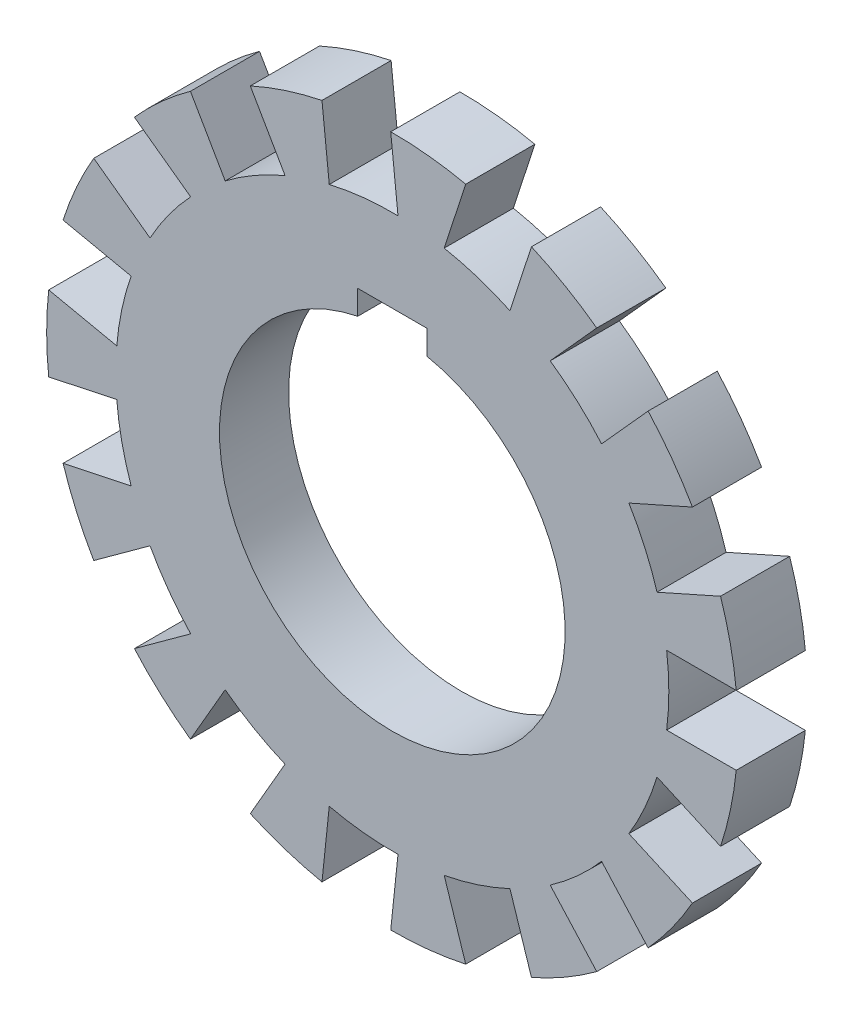
SolidWorks part; units mm, degrees
material "6061-T6 (SS)"
ref_plane "Front Plane" through (0, 0, 0) normal (0, 0, 1) x (1, 0, 0)
ref_plane "Top Plane" through (0, 0, 0) normal (0, 1, 0) x (1, 0, 0)
ref_plane "Right Plane" through (0, 0, 0) normal (1, 0, 0) x (0, 0, -1)
sketch "Sketch1" plane through (0, 0, 0) normal (0, 0, 1) x (1, 0, 0)
  line L0 (39.6863, -5) -> (49.7494, -5)
  line L1 (39.6863, 5) -> (49.7494, 5)
  line L2 (38.2889, -11.5741) -> (47.482, -15.6672)
  line L3 (34.2215, -20.7096) -> (43.4146, -24.8026)
  line L4 (30.271, -26.147) -> (37.0046, -33.6253)
  line L5 (22.8396, -32.8383) -> (29.5731, -40.3166)
  line L6 (17.019, -36.1988) -> (20.1287, -45.7694)
  line L7 (7.5084, -39.289) -> (10.6181, -48.8595)
  line L8 (0.8243, -39.9915) -> (-0.2276, -49.9995)
  line L9 (-9.121, -38.9462) -> (-10.1728, -48.9542)
  line L10 (-15.513, -36.8693) -> (-20.5446, -45.5842)
  line L11 (-24.1733, -31.8693) -> (-29.2048, -40.5842)
  line L12 (-29.1679, -27.3721) -> (-37.3092, -33.287)
  line L13 (-35.0458, -19.2819) -> (-43.187, -25.1969)
  line L14 (-37.7795, -13.142) -> (-47.6227, -15.2342)
  line L15 (-39.8586, -3.3605) -> (-49.7018, -5.4527)
  line L16 (-39.8586, 3.3605) -> (-49.7018, 5.4527)
  line L17 (-37.7795, 13.142) -> (-47.6227, 15.2342)
  line L18 (-35.0458, 19.2819) -> (-43.187, 25.1969)
  line L19 (-29.1679, 27.3721) -> (-37.3092, 33.287)
  line L20 (-24.1733, 31.8693) -> (-29.2048, 40.5842)
  line L21 (-15.513, 36.8693) -> (-20.5446, 45.5842)
  line L22 (-9.121, 38.9462) -> (-10.1728, 48.9542)
  line L23 (0.8243, 39.9915) -> (-0.2276, 49.9995)
  line L24 (7.5084, 39.289) -> (10.6181, 48.8595)
  line L25 (17.019, 36.1988) -> (20.1287, 45.7694)
  line L26 (22.8396, 32.8383) -> (29.5731, 40.3166)
  line L27 (30.271, 26.147) -> (37.0046, 33.6253)
  line L28 (34.2215, 20.7096) -> (43.4146, 24.8026)
  line L29 (38.2889, 11.5741) -> (47.482, 15.6672)
  line L30 (-5, 24.4949) -> (-5, 28)
  line L31 (-5, 28) -> (5, 28)
  line L32 (5, 28) -> (5, 24.4949)
  arc A0 (39.6863, -5) -> (39.6863, 5) centre (0, 0) ccw
  arc A1 (-5, 24.4949) -> (5, 24.4949) centre (0, 0) ccw
  arc A2 (49.7494, 5) -> (47.482, 15.6672) centre (0, 0) ccw
  arc A3 (43.4146, 24.8026) -> (37.0046, 33.6253) centre (0, 0) ccw
  arc A4 (29.5731, 40.3166) -> (20.1287, 45.7694) centre (0, 0) ccw
  arc A5 (10.6181, 48.8595) -> (-0.2276, 49.9995) centre (0, 0) ccw
  arc A6 (-10.1728, 48.9542) -> (-20.5446, 45.5842) centre (0, 0) ccw
  arc A7 (-29.2048, 40.5842) -> (-37.3092, 33.287) centre (0, 0) ccw
  arc A8 (-43.187, 25.1969) -> (-47.6227, 15.2342) centre (0, 0) ccw
  arc A9 (-49.7018, 5.4527) -> (-49.7018, -5.4527) centre (0, 0) ccw
  arc A10 (-47.6227, -15.2342) -> (-43.187, -25.1969) centre (0, 0) ccw
  arc A11 (-37.3092, -33.287) -> (-29.2048, -40.5842) centre (0, 0) ccw
  arc A12 (-20.5446, -45.5842) -> (-10.1728, -48.9542) centre (0, 0) ccw
  arc A13 (-0.2276, -49.9995) -> (10.6181, -48.8595) centre (0, 0) ccw
  arc A14 (20.1287, -45.7694) -> (29.5731, -40.3166) centre (0, 0) ccw
  arc A15 (37.0046, -33.6253) -> (43.4146, -24.8026) centre (0, 0) ccw
  arc A16 (47.482, -15.6672) -> (49.7494, -5) centre (0, 0) ccw
  arc A17 (38.2889, 11.5741) -> (34.2215, 20.7096) centre (0, 0) ccw
  arc A18 (30.271, 26.147) -> (22.8396, 32.8383) centre (0, 0) ccw
  arc A19 (17.019, 36.1988) -> (7.5084, 39.289) centre (0, 0) ccw
  arc A20 (0.8243, 39.9915) -> (-9.121, 38.9462) centre (0, 0) ccw
  arc A21 (-15.513, 36.8693) -> (-24.1733, 31.8693) centre (0, 0) ccw
  arc A22 (-29.1679, 27.3721) -> (-35.0458, 19.2819) centre (0, 0) ccw
  arc A23 (-37.7795, 13.142) -> (-39.8586, 3.3605) centre (0, 0) ccw
  arc A24 (-39.8586, -3.3605) -> (-37.7795, -13.142) centre (0, 0) ccw
  arc A25 (-35.0458, -19.2819) -> (-29.1679, -27.3721) centre (0, 0) ccw
  arc A26 (-24.1733, -31.8693) -> (-15.513, -36.8693) centre (0, 0) ccw
  arc A27 (-9.121, -38.9462) -> (0.8243, -39.9915) centre (0, 0) ccw
  arc A28 (7.5084, -39.289) -> (17.019, -36.1988) centre (0, 0) ccw
  arc A29 (22.8396, -32.8383) -> (30.271, -26.147) centre (0, 0) ccw
  arc A30 (34.2215, -20.7096) -> (38.2889, -11.5741) centre (0, 0) ccw
  point P11 (0, 28)
  dimension "D1" = 80
  dimension "D2" = 50
  dimension "D5" = 100
  dimension "D3" = 10
  dimension "D4" = 5
  dimension "D6" = 15
  dimension "D7" = 28
  dimension "D8" = 10
extrude "Boss-Extrude2" add sketch "Sketch1" along normal blind 10
